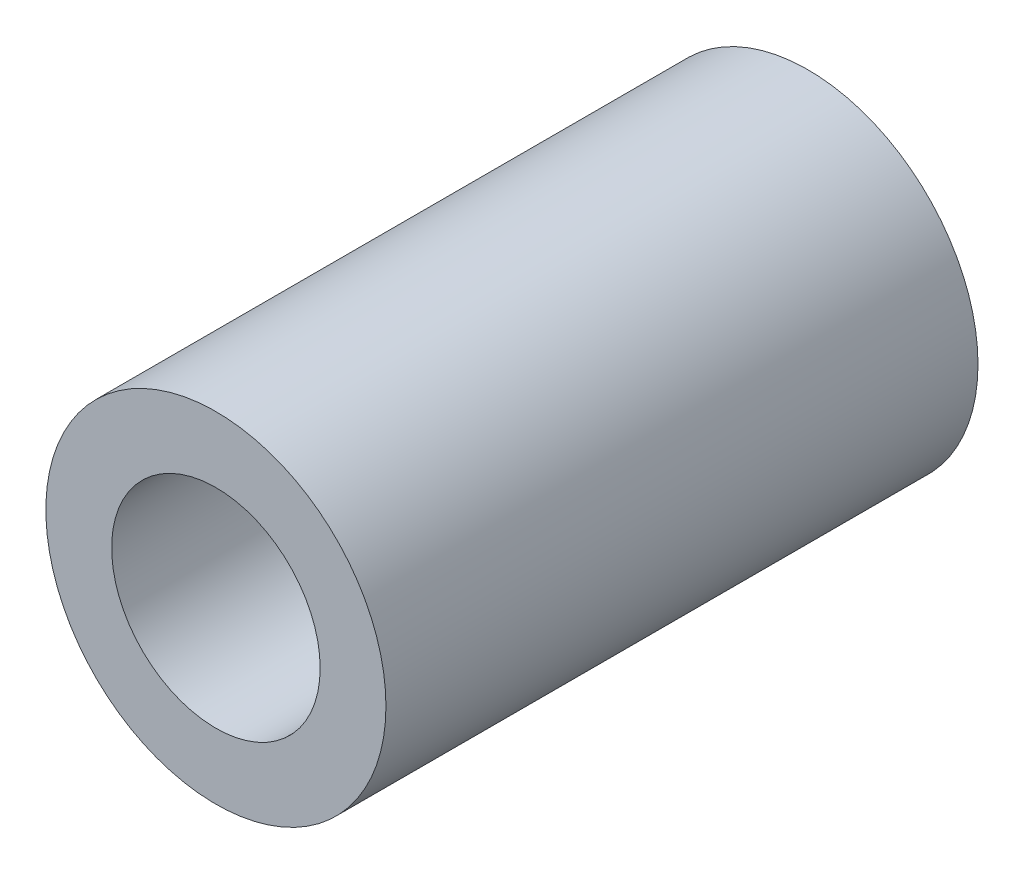
SolidWorks part; units mm, degrees
ref_plane "前视基准面" through (0, 0, 0) normal (0, 0, 1) x (1, 0, 0)
ref_plane "上视基准面" through (0, 0, 0) normal (0, 1, 0) x (1, 0, 0)
ref_plane "右视基准面" through (0, 0, 0) normal (1, 0, 0) x (0, 0, -1)
sketch "草图1" plane through (0, 0, 0) normal (0, 0, 1) x (1, 0, 0)
  circle A0 centre (0, 0) radius 1.585
  circle A1 centre (0, 0) radius 2.585
  dimension "D1" = 3.17
  dimension "D2" = 1
extrude "凸台-拉伸1" add sketch "草图1" along normal blind 9
